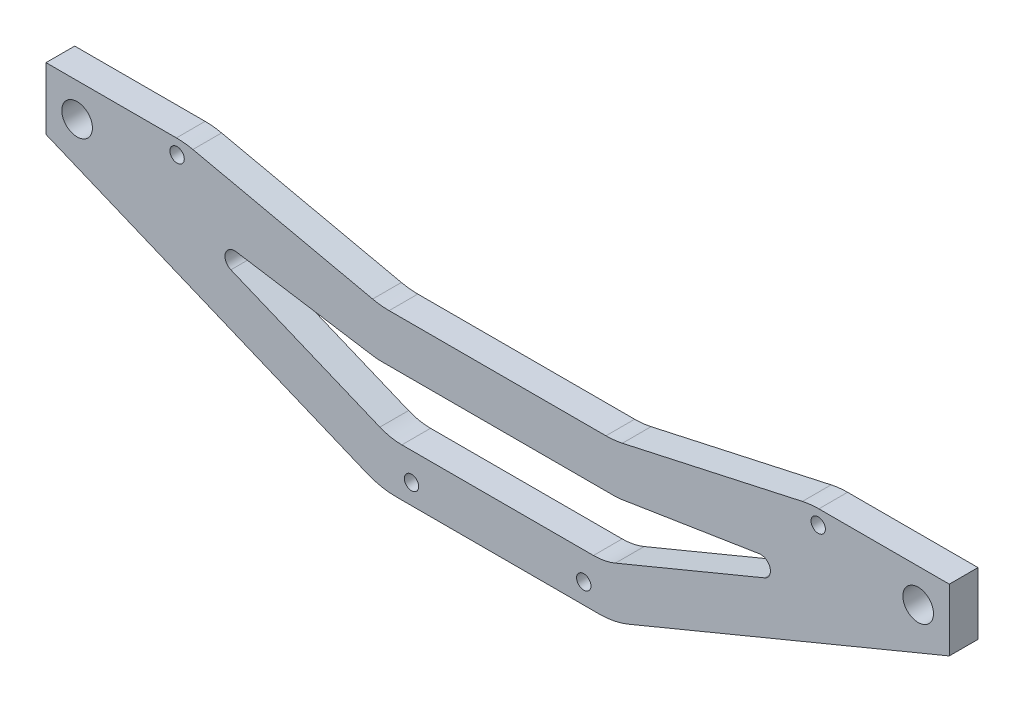
SolidWorks part; units mm, degrees
material "ABS"
ref_plane "Plano frontal" through (0, 0, 0) normal (0, 0, 1) x (1, 0, 0)
ref_plane "Plano superior" through (0, 0, 0) normal (0, 1, 0) x (1, 0, 0)
ref_plane "Plano direito" through (0, 0, 0) normal (1, 0, 0) x (0, 0, -1)
sketch "Esboço1" plane through (0, 0, 0) normal (0, 0, 1) x (1, 0, 0)
  line L0 (78.1151, 18.654) -> (78.1151, 12.154)
  line L1 (78.1151, 12.154) -> (43.1151, -2.346)
  line L2 (43.1151, -2.346) -> (18.7151, -2.346)
  line L3 (18.7151, -2.346) -> (-16.2849, 12.154)
  line L4 (-16.2849, 12.154) -> (-16.2849, 18.654)
  line L5 (-16.2849, 18.654) -> (-9.7849, 18.654)
  line L6 (71.6151, 18.654) -> (78.1151, 18.654)
  line L8 (43.1025, 14.1381) -> (18.7025, 14.1381)
  line L10 (19.7098, 2.654) -> (-4.7737, 12.7972)
  line L11 (-4.7737, 12.7972) -> (-4.7737, 12.7972)
  line L12 (-4.7737, 12.7972) -> (-4.7737, 12.7972)
  line L13 (18.3087, 9.1381) -> (-4.7737, 12.7972)
  line L14 (43.496, 9.1381) -> (18.3087, 9.1381)
  line L15 (66.6071, 12.7985) -> (43.496, 9.1381)
  line L16 (66.6071, 12.7985) -> (66.6071, 12.7985)
  line L17 (66.6071, 12.7985) -> (66.6071, 12.7985)
  line L18 (66.6071, 12.7985) -> (42.1204, 2.654)
  line L19 (42.1204, 2.654) -> (19.7098, 2.654)
  line L20 (18.7025, 14.1381) -> (-9.7849, 18.654) construction
  line L21 (71.6151, 18.654) -> (43.1025, 14.1381) construction
  line L22 (18.7025, 14.1381) -> (-1.7849, 18.654)
  line L23 (-1.7849, 18.654) -> (-9.7849, 18.654)
  line L24 (43.1025, 14.1381) -> (63.6151, 18.654)
  line L25 (63.6151, 18.654) -> (71.6151, 18.654)
  circle A0 centre (74.8651, 15.154) radius 1.6
  circle A1 centre (-13.0349, 15.154) radius 1.6
  circle A2 centre (21.9151, -0.246) radius 0.75
  circle A3 centre (39.9151, -0.246) radius 0.75
  circle A4 centre (64.4151, 17.154) radius 0.75
  circle A5 centre (-2.5849, 17.154) radius 0.75
  dimension "D1" = 35
  dimension "D2" = 35
  dimension "D3" = 21
  dimension "D4" = 8
  dimension "D5" = 4.516
  dimension "D7" = 8
  dimension "D6" = 5
extrude "Ressalto-extrusão1" add sketch "Esboço1" along normal blind 3
fillet "Filete1" radius 1 2 edges at (-4.7737, 12.7972, 1.5) (66.6071, 12.7985, 1.5)
fillet "Filete2" radius 6 4 edges at (43.496, 9.1381, 1.5) (18.3087, 9.1381, 1.5) (19.7098, 2.654, 1.5) (42.1204, 2.654, 1.5)
fillet "Filete3" radius 8 4 edges at (43.1151, -2.346, 1.5) (18.7151, -2.346, 1.5) (18.7025, 14.1381, 1.5) (43.1025, 14.1381, 1.5)
fillet "Filete4" radius 8 2 edges at (63.6151, 18.654, 1.5) (-1.7849, 18.654, 1.5)
